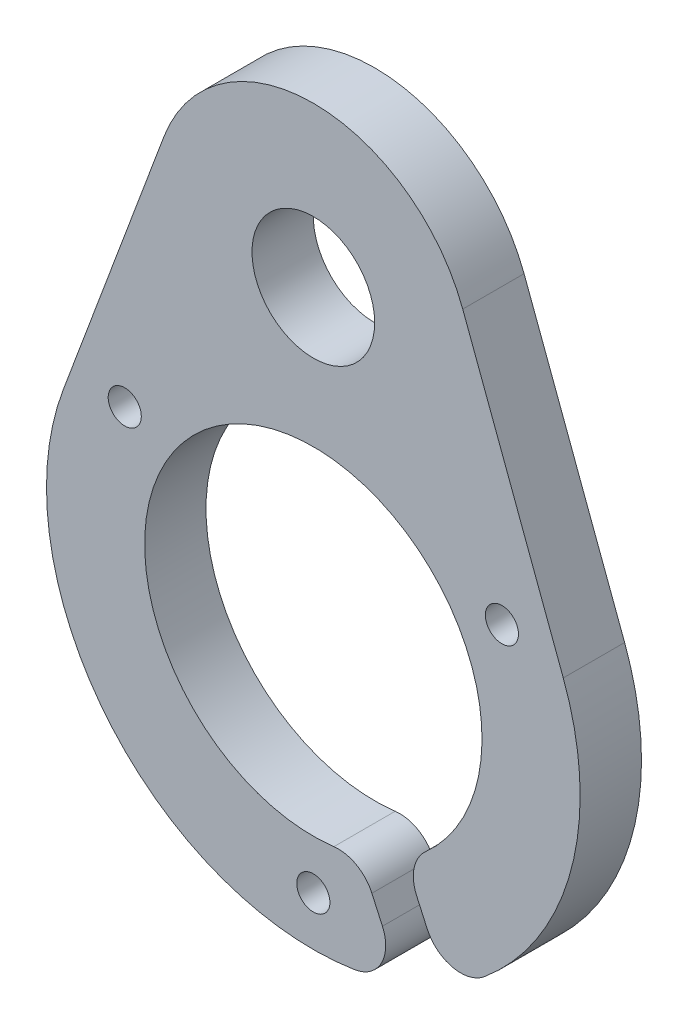
SolidWorks part; units mm, degrees
ref_plane "Front Plane" through (0, 0, 0) normal (0, 0, 1) x (1, 0, 0)
ref_plane "Top Plane" through (0, 0, 0) normal (0, 1, 0) x (1, 0, 0)
ref_plane "Right Plane" through (0, 0, 0) normal (1, 0, 0) x (0, 0, -1)
sketch "Sketch1" plane through (0, 0, 0) normal (0, 0, 1) x (1, 0, 0)
  line L0 (7.434, -11.5671) -> (10.7566, -18.9039)
  line L23 (3.7902, -13.2173) -> (7.1128, -20.5541)
  line L46 (0, 0) -> (8.9727, -19.8129) construction
  line L47 (0, 0) -> (24.8053, 0) construction
  line L48 (12.1777, 29.55) -> (20.3743, 7.6125) construction
  line L53 (0, 0) -> (0, 25) construction
  line L54 (-12.1777, 29.55) -> (-20.3743, 7.6125) construction
  line L59 (-20.3743, 7.6125) -> (-12.1777, 29.55)
  line L60 (12.1777, 29.55) -> (20.3743, 7.6125)
  line L63 (15.372, 8.875) -> (0, 0) construction
  line L64 (0, 0) -> (-15.372, 8.875) construction
  circle A10 centre (0, 0) radius 13.75 construction
  arc A11 (3.7902, -13.2173) -> (7.434, -11.5671) centre (0, 0) cw
  circle A12 centre (0, 0) radius 21.75 construction
  circle A13 centre (0, 25) radius 5
  circle A14 centre (0, 25) radius 13 construction
  arc A15 (-12.1777, 29.55) -> (12.1777, 29.55) centre (0, 25) cw
  arc A18 (10.7566, -18.9039) -> (20.3743, 7.6125) centre (0, 0) ccw
  circle A19 centre (0, -17.75) radius 1.35
  arc A21 (-20.3743, 7.6125) -> (7.1128, -20.5541) centre (0, 0) ccw
  circle A22 centre (0, 0) radius 17.75 construction
  circle A23 centre (15.372, 8.875) radius 1.35
  circle A24 centre (-15.372, 8.875) radius 1.35
  circle A25 centre (0, 25) radius 9.5 construction
  circle A26 centre (0, 0) radius 15 construction
  point P15 (7.434, -11.5671)
  point P16 (3.7902, -13.2173)
  dimension "D2" = 10
  dimension "D1" = 27.5
  dimension "D10" = 60
  dimension "D4" = 8
  dimension "D5" = 8
  dimension "D8" = 2.7
  dimension "D6" = 4
  dimension "D9" = 19
  dimension "D11" = 30
  dimension "D3" = 25
  dimension "D7" = 4
extrude "Boss-Extrude1" add sketch "Sketch1" along normal blind 5
fillet "Congé2" radius 3 4 edges at (10.7566, -18.9039, 2.5) (3.7902, -13.2173, 2.5) (7.434, -11.5671, 2.5) (7.1128, -20.5541, 2.5)
